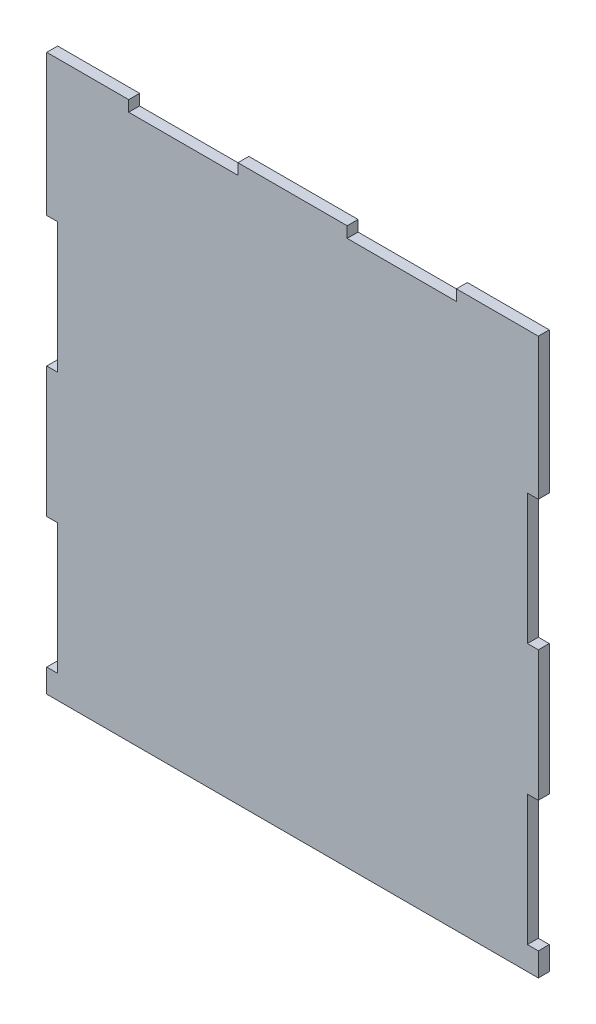
SolidWorks part; units mm, degrees
ref_plane "Front Plane" through (0, 0, 0) normal (0, 0, 1) x (1, 0, 0)
ref_plane "Top Plane" through (0, 0, 0) normal (0, 1, 0) x (1, 0, 0)
ref_plane "Right Plane" through (0, 0, 0) normal (1, 0, 0) x (0, 0, -1)
sketch "Sketch1" plane through (0, 0, 0) normal (0, 0, 1) x (1, 0, 0)
  line L1 (0, 0) -> (129, 0)
  line L2 (0, 6.45) -> (0, 42.25)
  line L3 (19.5, 149.65) -> (49.5, 149.65)
  line L4 (129, 6.45) -> (129, 42.25)
  line L5 (0, 152.65) -> (19.5, 152.65)
  line L6 (19.5, 152.65) -> (19.5, 149.65)
  line L7 (49.5, 149.65) -> (49.5, 152.65)
  line L8 (49.5, 152.65) -> (79.5, 152.65)
  line L9 (79.5, 152.65) -> (79.5, 149.65)
  line L11 (129, 152.65) -> (109.5, 152.65)
  line L12 (109.5, 152.65) -> (109.5, 149.65)
  line L13 (79.5, 149.65) -> (109.5, 149.65)
  line L15 (132, 149.65) -> (132, 113.85)
  line L16 (132, 113.85) -> (129, 113.85)
  line L17 (129, 78.05) -> (132, 78.05)
  line L18 (132, 78.05) -> (132, 42.25)
  line L19 (132, 42.25) -> (129, 42.25)
  line L20 (129, 6.45) -> (132, 6.45)
  line L21 (132, 6.45) -> (132, 0)
  line L22 (129, 78.05) -> (129, 113.85)
  line L23 (129, 0) -> (132, 0)
  line L24 (132, 149.65) -> (132, 152.65)
  line L25 (132, -29.35) -> (129, -29.35) [skipped]
  line L26 (132, 152.65) -> (129, 152.65)
  line L28 (-3, 149.65) -> (-3, 113.85)
  line L29 (-3, 113.85) -> (0, 113.85)
  line L30 (0, 78.05) -> (-3, 78.05)
  line L31 (-3, 78.05) -> (-3, 42.25)
  line L32 (-3, 42.25) -> (0, 42.25)
  line L33 (0, 6.45) -> (-3, 6.45)
  line L34 (-3, 6.45) -> (-3, 0)
  line L35 (0, 152.65) -> (-3, 152.65)
  line L36 (0, 78.05) -> (0, 113.85)
  line L37 (0, 0) -> (-3, 0)
  line L38 (-3, 152.65) -> (-3, 149.65)
  dimension "D3" = 19.5
  dimension "D5" = 30
  dimension "D6" = 3
  dimension "D7" = 30
  dimension "D8" = 3
  dimension "D9" = 19.5
  dimension "D10" = 35.8
  dimension "D11" = 35.8
  dimension "D12" = 3
extrude "Boss-Extrude1" add sketch "Sketch1" along normal blind 3
